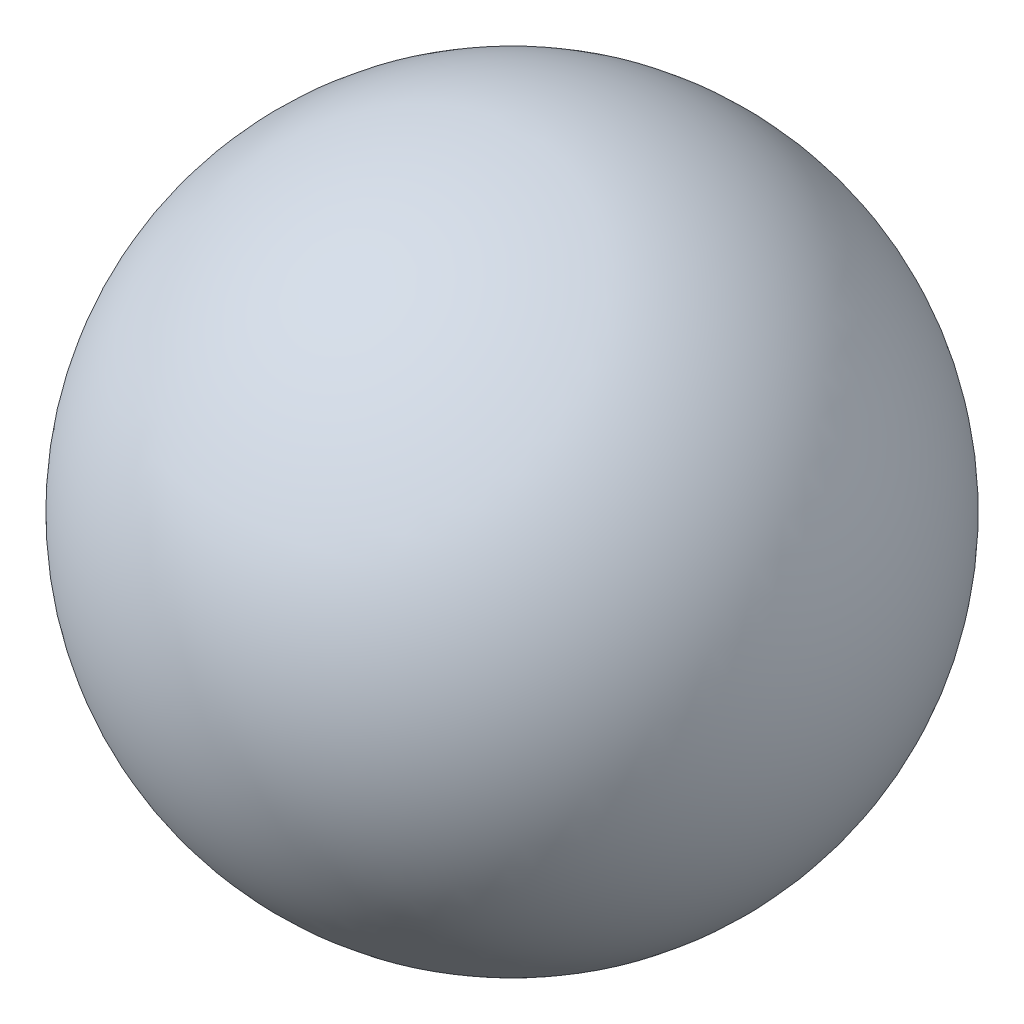
SolidWorks part; units mm, degrees
ref_plane "Front Plane" through (0, 0, 0) normal (0, 0, 1) x (1, 0, 0)
ref_plane "Top Plane" through (0, 0, 0) normal (0, 1, 0) x (1, 0, 0)
ref_plane "Right Plane" through (0, 0, 0) normal (1, 0, 0) x (0, 0, -1)
sketch "Sketch1" plane through (0, 0, 0) normal (0, 0, 1) x (1, 0, 0)
  line L0 (-8.0484, 79.367) -> (-8.0484, -23.0284)
  arc A0 (-8.0484, -23.0284) -> (-8.0484, 79.367) centre (-8.0484, 28.1693) ccw
revolve "Revolve1" add sketch "Sketch1" angle 360 about L0
scale "Scale1" scale about centroid uniform scaling yes scale factor 0.5
